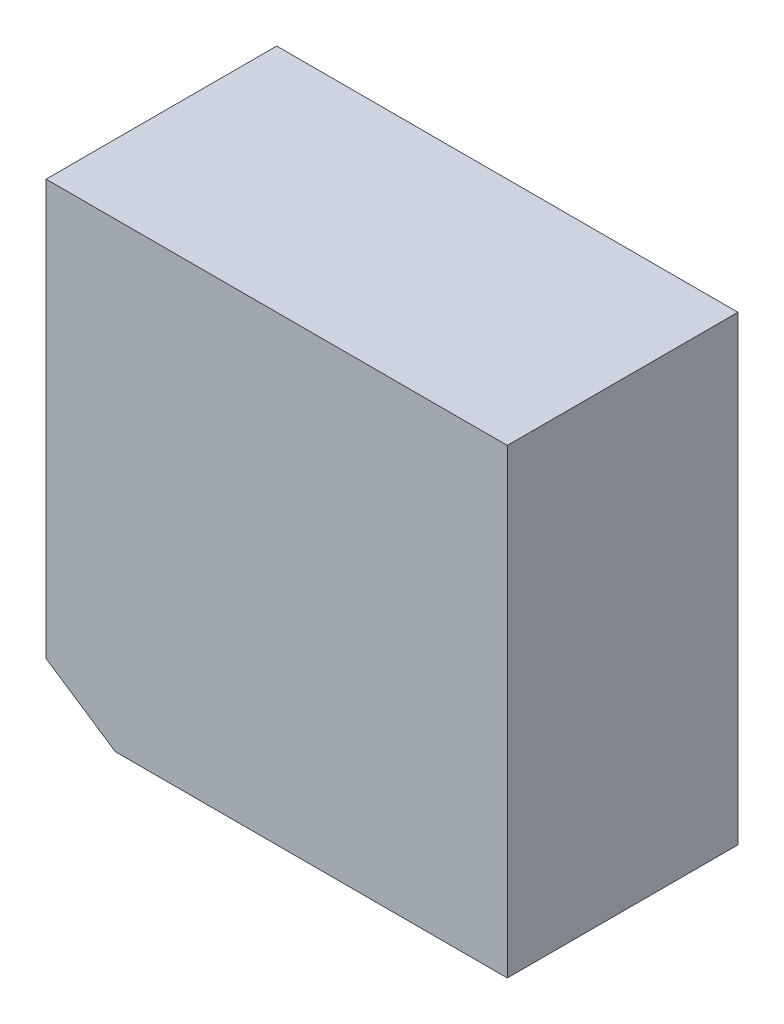
SolidWorks part; units mm, degrees
ref_plane "前视基准面" through (0, 0, 0) normal (0, 0, 1) x (1, 0, 0)
ref_plane "上视基准面" through (0, 0, 0) normal (0, 1, 0) x (1, 0, 0)
ref_plane "右视基准面" through (0, 0, 0) normal (1, 0, 0) x (0, 0, -1)
other "Configuration Table"
sketch "草图1" plane through (0, 0, 0) normal (0, 0, 1) x (1, 0, 0)
  line L1 (0, 0) -> (20, 0)
  line L2 (0, 0) -> (0, 20)
  line L3 (0, 20) -> (20, 20)
  line L4 (20, 0) -> (20, 20)
extrude "BaseBox" add sketch "草图1" along normal blind 10
chamfer "ChamferDistanceDistance" distance 2 distance2 3 1 edges at (0, 0, 5)
